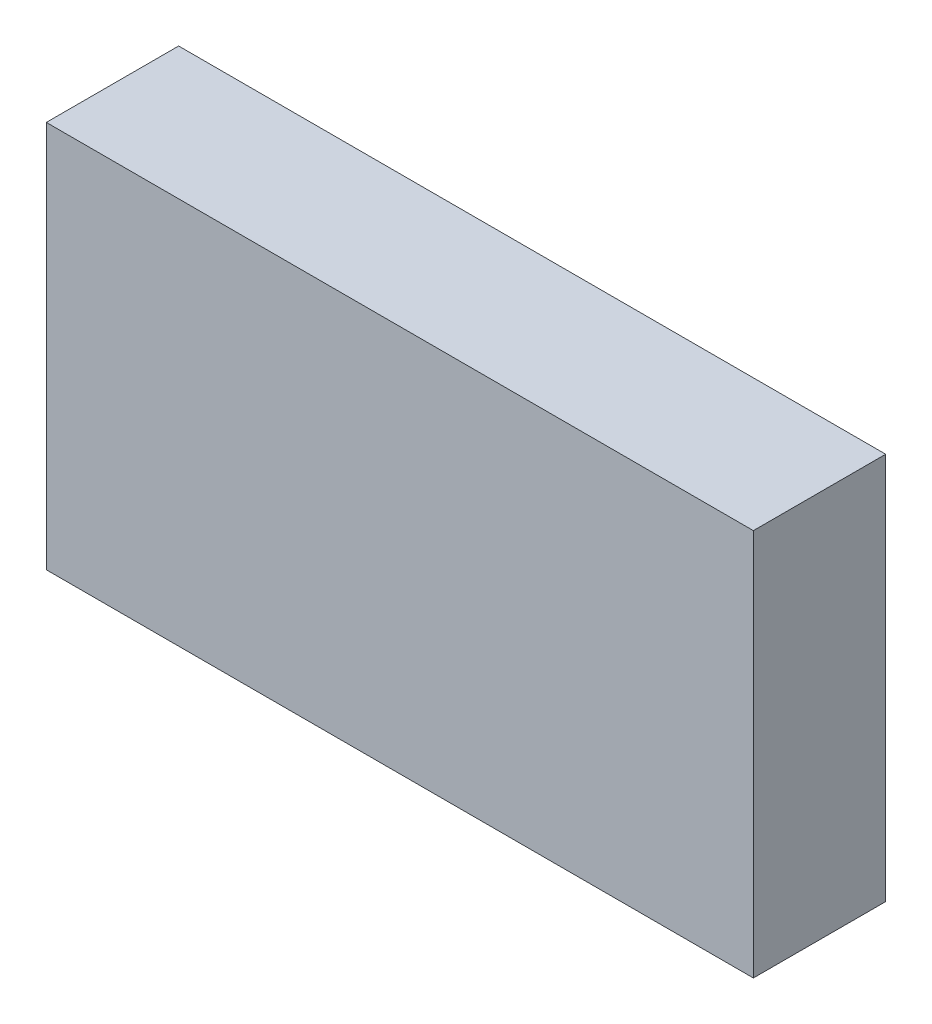
SolidWorks part; units mm, degrees
ref_plane "Front Plane" through (0, 0, 0) normal (0, 0, 1) x (1, 0, 0)
ref_plane "Top Plane" through (0, 0, 0) normal (0, 1, 0) x (1, 0, 0)
ref_plane "Right Plane" through (0, 0, 0) normal (1, 0, 0) x (0, 0, -1)
sketch "CurveSketch" plane through (0, 0, 0) normal (0, 0, 1) x (1, 0, 0)
  line L0 (-20.0525, -1.8635) -> (11.6665, -1.8635)
  line L1 (11.6665, -1.8635) -> (11.6665, 15.5175)
  line L2 (11.6665, 15.5175) -> (-20.0525, 15.5175)
  line L3 (-20.0525, 15.5175) -> (-20.0525, -1.8635)
extrude "CurveBoss" add sketch "CurveSketch" along normal blind 2.317 and the other way blind 3.619
